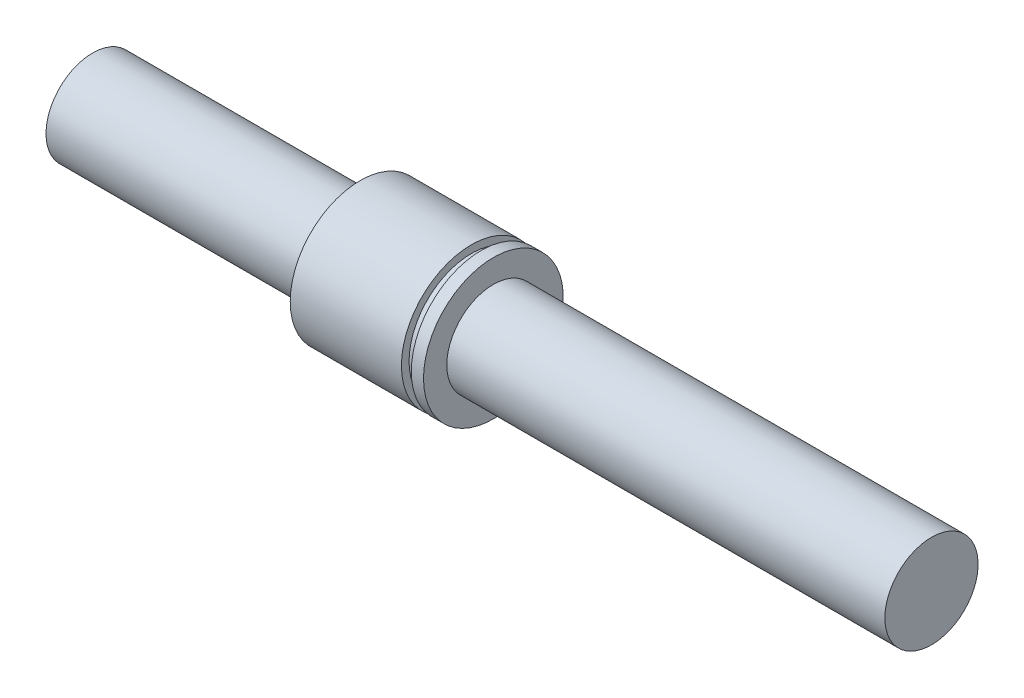
SolidWorks part; units mm, degrees
material "AISI 1020"
ref_plane "Front Plane" through (0, 0, 0) normal (0, 0, 1) x (1, 0, 0)
ref_plane "Top Plane" through (0, 0, 0) normal (0, 1, 0) x (1, 0, 0)
ref_plane "Right Plane" through (0, 0, 0) normal (1, 0, 0) x (0, 0, -1)
sketch "Sketch1" plane through (0, 0, 0) normal (0, 0, 1) x (1, 0, 0)
  line L1 (-63.1866, 5.6564) -> (-63.1866, 0.6564)
  line L2 (-63.1866, 0.6564) -> (26.8134, 0.6564)
  line L3 (26.8134, 0.6564) -> (26.8134, 5.6564)
  line L7 (26.8134, 5.6564) -> (-20.1866, 5.6564)
  line L8 (-20.1866, 8.1564) -> (-21.4971, 8.1564)
  line L9 (-34.4844, 8.1564) -> (-34.4844, 5.6564)
  line L10 (-20.1866, 8.1564) -> (-20.1866, 5.6564)
  line L11 (-34.4844, 5.6564) -> (-63.1866, 5.6564)
  line L12 (-22.5546, 8.1564) -> (-34.4844, 8.1564)
  line L14 (-21.4971, 8.1564) -> (-21.4971, 7.3381)
  line L15 (-21.4971, 7.3381) -> (-22.5546, 7.3381)
  line L16 (-22.5546, 8.1564) -> (-22.5546, 7.3381)
  line L17 (26.8134, -10.3436) -> (26.8134, 11.6564) construction
  dimension "D1" = 5
  dimension "D2" = 7.5
  dimension "D3" = 90
revolve "Revolve1" add sketch "Sketch1" angle 360 about L2
